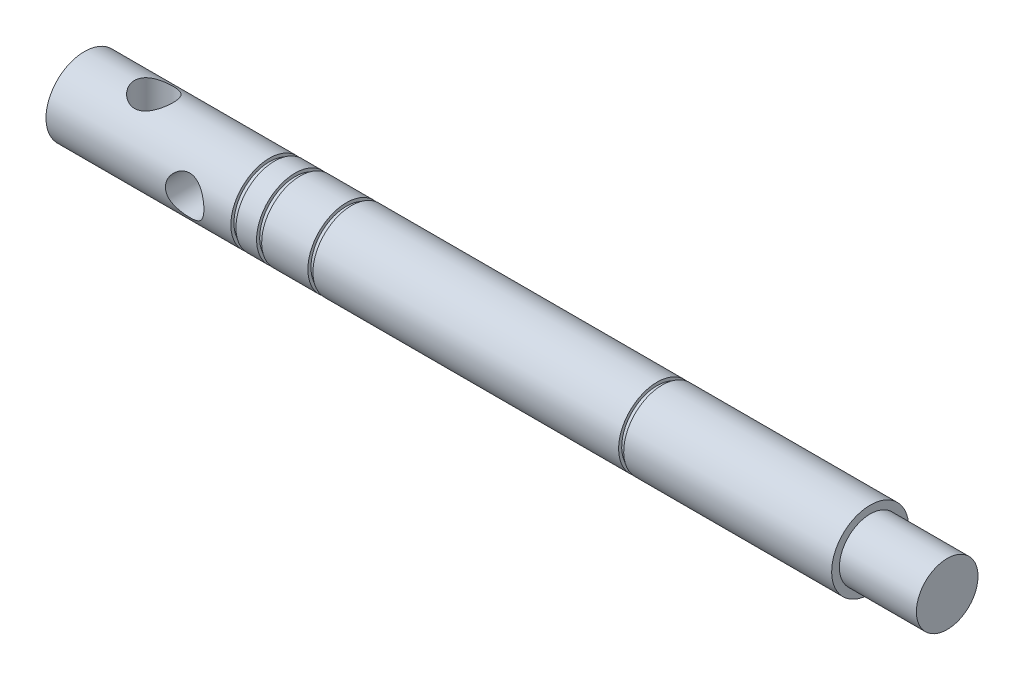
SolidWorks part; units mm, degrees
material "AISI 1020"
ref_plane "Front Plane" through (0, 0, 0) normal (0, 0, 1) x (1, 0, 0)
ref_plane "Top Plane" through (0, 0, 0) normal (0, 1, 0) x (1, 0, 0)
ref_plane "Right Plane" through (0, 0, 0) normal (1, 0, 0) x (0, 0, -1)
sketch "Sketch1" plane through (0, 0, 0) normal (0, 0, 1) x (1, 0, 0)
  line L0 (0, 0) -> (0, 4)
  line L1 (0, 4) -> (-10, 4)
  line L2 (-10, 4) -> (-10, 5)
  line L3 (-10, 5) -> (-37, 5)
  line L4 (-84, 5) -> (-84, 4.6)
  line L5 (-84, 4.6) -> (-84.66, 4.6)
  line L6 (-112, 5) -> (-112, 0)
  line L7 (0, 0) -> (-112, 0) construction
  line L8 (0, 0) -> (-112, 0)
  line L13 (-84.66, 4.6) -> (-84.66, 5)
  line L14 (-84.66, 5) -> (-87.34, 5)
  line L16 (-78, 5) -> (-78, 4.6)
  line L17 (-78, 4.6) -> (-77.34, 4.6)
  line L18 (-77.34, 4.6) -> (-77.34, 5)
  line L19 (-78, 5) -> (-84, 5)
  line L20 (-37, 5) -> (-37, 4.6)
  line L21 (-37, 4.6) -> (-37.66, 4.6)
  line L22 (-37.66, 4.6) -> (-37.66, 5)
  line L23 (-37.66, 5) -> (-77.34, 5)
  line L24 (-87.34, 5) -> (-87.34, 4.6)
  line L25 (-87.34, 4.6) -> (-88, 4.6)
  line L26 (-88, 4.6) -> (-88, 5)
  line L27 (-88, 5) -> (-112, 5)
  dimension "D2" = 5
  dimension "D3" = 4
  dimension "D4" = 112
  dimension "D5" = 78
  dimension "D6" = 10
  dimension "D7" = 41
  dimension "D8" = 4
  dimension "D10" = 5
  dimension "D11" = 0.66
  dimension "D12" = 0.4
  dimension "D13" = 0.66
  dimension "D14" = 0.4
  dimension "D15" = 6
revolve "Revolve1" add sketch "Sketch1" angle 360 about L7
sketch "Sketch2" plane through (0, 0, 0) normal (0, 1, 0) x (1, 0, 0)
  line L0 (-88, -5) -> (-88, 5) construction
  circle A0 centre (-103, 0) radius 2.5
  dimension "D2" = 5
  dimension "D1" = 15
extrude "Cut-Extrude1" cut sketch "Sketch2" against normal through all both and the other way through all
sketch "Sketch4" plane through (0, 0, 0) normal (0, 0, 1) x (1, 0, 0)
  line L1 (-88, -5) -> (-88, 5) construction
  circle A0 centre (-94, 0) radius 2.5
  dimension "D1" = 5
  dimension "D2" = 6
extrude "Cut-Extrude2" cut sketch "Sketch4" against normal through all both and the other way through all
sketch "Sketch5" plane through (0, 0, 0) normal (1, 0, 0) x (0, 0, -1)
  line L0 (0, 0) -> (-1.1495, -3.8313)
  circle A0 centre (0, 0) radius 4 construction
